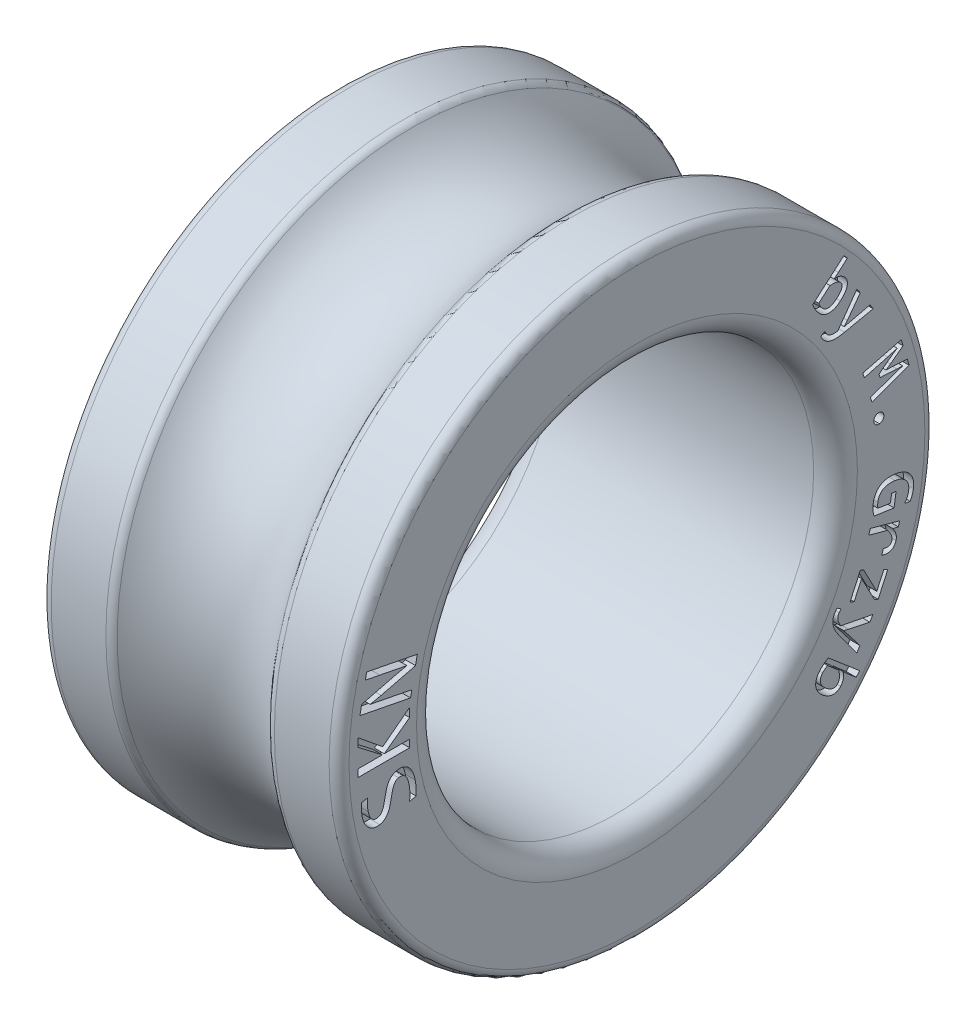
SolidWorks part; units mm, degrees
ref_plane "Front Plane" through (0, 0, 0) normal (1, 0, 0) x (0, 1, 0)
ref_plane "Top Plane" through (0, 0, 0) normal (0, 0, 1) x (0, 1, 0)
ref_plane "Right Plane" through (0, 0, 0) normal (0, 1, 0) x (-1, 0, 0)
sketch "Sketch2" plane through (0, 0, 0) normal (0, 1, 0) x (-1, 0, 0)
  line L0 (-14.359, 0) -> (14.359, 0) construction
  line L1 (-7.5, 15) -> (-7.5, 10)
  line L2 (-7.5, 10) -> (7.5, 10)
  line L3 (7.5, 10) -> (7.5, 15)
  line L4 (7.5, 15) -> (4, 15)
  line L5 (-4, 15) -> (-7.5, 15)
  arc A0 (-4, 15) -> (4, 15) centre (0, 18) ccw
  point P2 (0, 0)
  point P10 (0, 10)
  dimension "D4" = 10
  dimension "D5" = 3
  dimension "D1" = 10
  dimension "D2" = 15
  dimension "D3" = 5
revolve "Revolve1" add sketch "Sketch2" angle 360 about L0
fillet "Fillet1" radius 1.1 2 edges at (7.5, 0, -10) (-7.5, 0, -10)
fillet "Fillet2" radius 0.5 2 edges at (-7.5, 0, -15) (7.5, 0, -15)
fillet "Fillet3" radius 0.5 2 edges at (-4, 0, -15) (4, 0, -15)
sketch "Sketch3" plane through (7.5, 0, 0) normal (1, 0, 0) x (0, 1, 0)
  arc A2 (4.4009, 10.6246) -> (-4.4009, 10.6246) centre (0, 0) ccw construction
  arc A3 (-12.0395, -1.2082) -> (12.0395, -1.2082) centre (0, 0) ccw construction
  text T0 "SKN" font "Consolas" height 2.6
  text T1 "by M. Grzyb" font "Consolas" height 2
  point P4 (0, -12.1)
  point P16 (0, 11.5)
  dimension "D1" = 11.5
  dimension "D2" = 12.1
extrude "Cut-Extrude1" cut sketch "Sketch3" against normal blind 0.5
